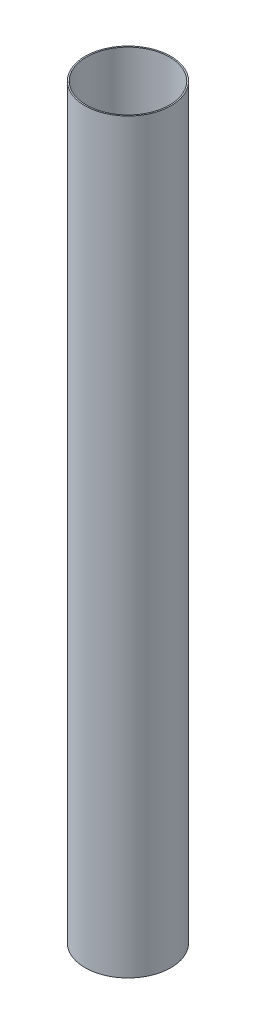
SolidWorks part; units mm, degrees
ref_plane "Front Plane" through (0, 0, 0) normal (0, 0, 1) x (1, 0, 0)
ref_plane "Top Plane" through (0, 0, 0) normal (0, 1, 0) x (1, 0, 0)
ref_plane "Right Plane" through (0, 0, 0) normal (1, 0, 0) x (0, 0, -1)
sketch "Sketch1" plane through (0, 0, 0) normal (0, 1, 0) x (1, 0, 0)
  circle A0 centre (0, 0) radius 51.1048
  circle A1 centre (0, 0) radius 49.53
  dimension "D1" = 99.06
  dimension "D2" = 102.2096
extrude "Boss-Extrude1" add sketch "Sketch1" along normal blind 889
